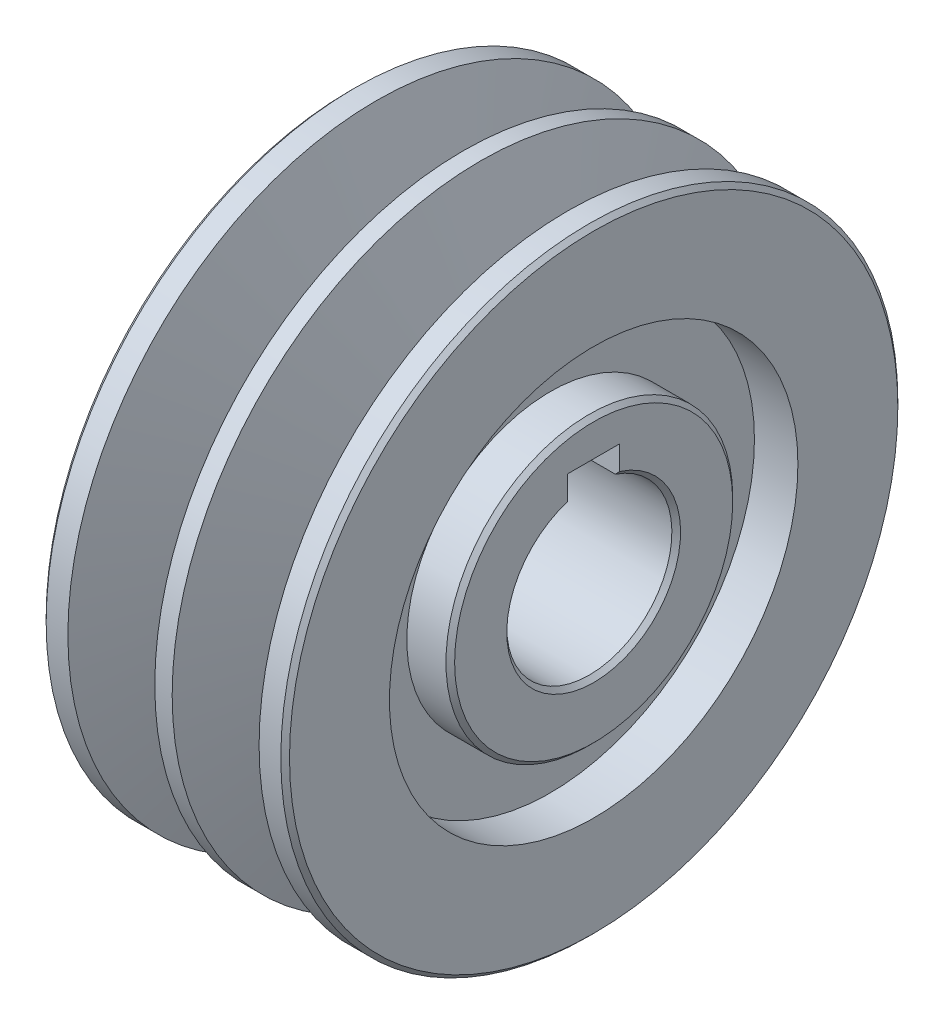
SolidWorks part; units mm, degrees
ref_plane "Front Plane" through (0, 0, 0) normal (0, 0, 1) x (1, 0, 0)
ref_plane "Top Plane" through (0, 0, 0) normal (0, 1, 0) x (1, 0, 0)
ref_plane "Right Plane" through (0, 0, 0) normal (1, 0, 0) x (0, 0, -1)
sketch "Sketch1" plane through (0, 0, 0) normal (0, 1, 0) x (1, 0, 0)
  line L0 (-14, 35.5) -> (-14, 23.5)
  line L1 (-14, 35.5) -> (-11, 35.5)
  line L2 (14, 35.5) -> (14, 23.5)
  line L3 (14, 23.5) -> (9, 23.5)
  line L4 (9, 23.5) -> (9, 16.5)
  line L5 (9, 16.5) -> (14, 16.5)
  line L6 (14, 16.5) -> (14, 9.5)
  line L7 (14, 9.5) -> (-14, 9.5)
  line L8 (-14, 9.5) -> (-14, 16.5)
  line L9 (-14, 16.5) -> (-9, 16.5)
  line L10 (-9, 16.5) -> (-9, 23.5)
  line L11 (-9, 23.5) -> (-14, 23.5)
  line L12 (0, 0) -> (0, 95.8906) construction
  line L13 (1, 35.5) -> (4.0573, 25.5)
  line L14 (4.0573, 25.5) -> (7.9427, 25.5)
  line L15 (7.9427, 25.5) -> (11, 35.5)
  line L16 (11, 35.5) -> (14, 35.5)
  line L17 (0, 0) -> (-42.3045, 0) construction
  line L18 (-11, 35.5) -> (-7.9427, 25.5)
  line L19 (-7.9427, 25.5) -> (-4.0573, 25.5)
  line L20 (-4.0573, 25.5) -> (-1, 35.5)
  line L21 (-1, 35.5) -> (1, 35.5)
  dimension "D1" = 10
  dimension "D2" = 10
  dimension "D3" = 34
  dimension "D4" = 28
  dimension "D5" = 28
  dimension "D6" = 5
  dimension "D7" = 7
  dimension "D8" = 9.5
  dimension "D9" = 35.5
  dimension "D10" = 12
  dimension "D11" = 10
  dimension "D12" = 34
  dimension "D13" = 34
  dimension "D14" = 2
revolve "Revolve1" add sketch "Sketch1" angle 360 about L17
chamfer "Chamfer1" distance 0.5 angle 45 3 edges at (14, 0, -9.5) (14, 0, -16.5) (14, 0, -35.5)
chamfer "Chamfer2" distance 0.5 angle 45 4 edges at (-14, 0, -16.5) (-14, 0, -9.5) (-14, 0, -35.5) (-14, 0, -23.5)
fillet "Fillet2" radius 1 2 edges at (-9, 0, -23.5) (-9, 0, -16.5)
sketch "Sketch2" plane through (14, 0, 0) normal (1, 0, 0) x (0, 0, -1)
  line L0 (-3, 12.3) -> (-3, 7.433)
  line L1 (-3, 12.3) -> (3, 12.3)
  line L4 (3, 12.3) -> (3, 9.5)
  line L7 (-3, 7.433) -> (3, 7.433)
  line L8 (3, 7.433) -> (3, 9.5)
  point P0 (0, 7.433)
  point P5 (0, 0)
  dimension "D1" = 2.8
  dimension "D2" = 6
  dimension "D3" = 12.3
extrude "Cut-Extrude1" cut sketch "Sketch2" against normal through all
